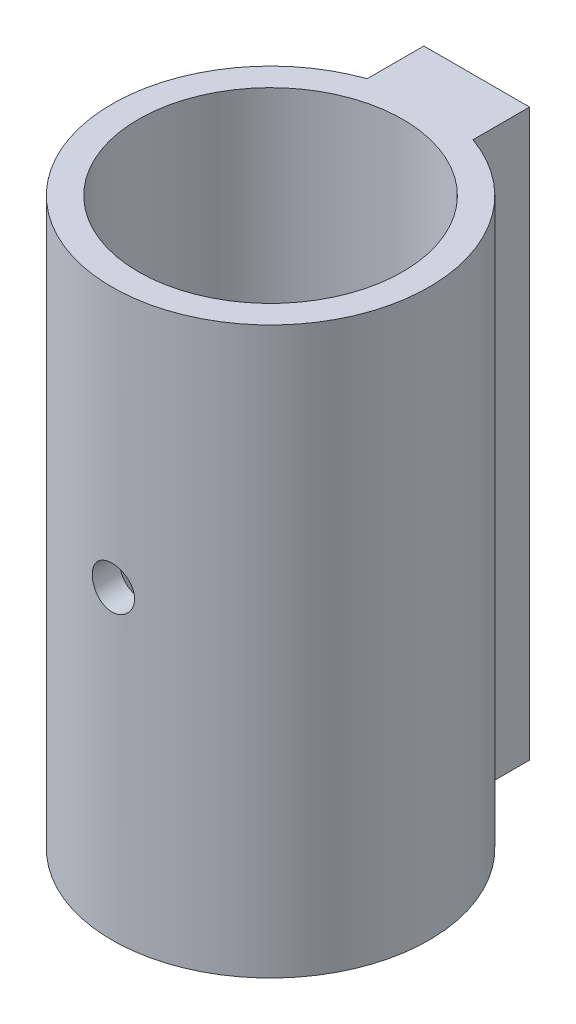
SolidWorks part; units mm, degrees
ref_plane "Front Plane" through (0, 0, 0) normal (0, 0, 1) x (1, 0, 0)
ref_plane "Top Plane" through (0, 0, 0) normal (0, 1, 0) x (1, 0, 0)
ref_plane "Right Plane" through (0, 0, 0) normal (1, 0, 0) x (0, 0, -1)
sketch "Sketch2" plane through (0, 0, 0) normal (0, 1, 0) x (1, 0, 0)
  line L0 (0, 7.8) -> (-2, 7.8)
  line L1 (-2, 7.8) -> (-2, 5.6569)
  line L2 (0, 7.8) -> (2, 7.8)
  line L3 (2, 7.8) -> (2, 5.6569)
  line L4 (-2.5415, -6) -> (44.0386, -6) construction
  line L5 (0, 0) -> (0, 7.8) construction
  arc A0 (-2, 5.6569) -> (2, 5.6569) centre (0, 0) ccw
  dimension "D1" = 6
  dimension "D2" = 4
  dimension "D3" = 13.8
extrude "Boss-Extrude1" add sketch "Sketch2" along normal blind 21.4
sketch "Sketch3" plane through (0, 21.4, 0) normal (0, 1, 0) x (1, 0, 0)
  circle A0 centre (0, 0) radius 5
  dimension "D1" = 10
extrude "Cut-Extrude1" cut sketch "Sketch3" against normal blind 24.9
sketch "Sketch4" plane through (0, 0, -7.8) normal (0, 0, -1) x (-1, 0, 0)
  line L0 (0, 21.4) -> (0, 0) construction
  line L1 (-2, 21.4) -> (2, 21.4) construction
  circle A0 centre (0, 11.5544) radius 1.99
  dimension "D1" = 3.98
extrude "Cut-Extrude2" cut sketch "Sketch4" against normal blind 2
sketch "Sketch5" plane through (0, 0, -5.8) normal (0, 0, -1) x (-1, 0, 0)
  circle A0 centre (0, 11.5544) radius 0.8
  dimension "D1" = 1.6
extrude "Cut-Extrude3" cut sketch "Sketch5" against normal through all
